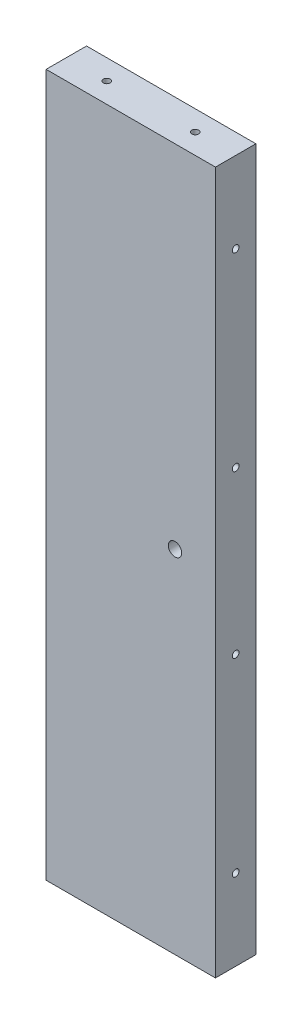
SolidWorks part; units mm, degrees
material "Beech"
ref_plane "Front Plane" through (0, 0, 0) normal (0, 0, 1) x (1, 0, 0)
ref_plane "Top Plane" through (0, 0, 0) normal (0, 1, 0) x (1, 0, 0)
ref_plane "Right Plane" through (0, 0, 0) normal (1, 0, 0) x (0, 0, -1)
sketch "Sketch1" plane through (0, 0, 0) normal (0, 0, 1) x (1, 0, 0)
  line L1 (209.353, 93.45) -> (289.1466, 93.45)
  line L2 (209.353, 93.45) -> (209.353, -237.5)
  line L3 (209.353, -237.5) -> (289.1466, -237.5)
  line L4 (289.1466, 93.45) -> (289.1466, -237.5)
  dimension "D1" = 79.7937
extrude "Boss-Extrude1" add sketch "Sketch1" along normal blind 19.05
hole_wizard "1/4 (0.25) Diameter Hole1" positions "Sketch10" profile "Sketch11" hole size "1/4" standard "ANSI Inch" end condition through all
sketch "Sketch10" plane through (0, 0, 0) normal (0, 0, -1) x (-1, 0, 0)
  point P0 (-270.0966, -72.025)
sketch "Sketch11" plane through (270.0966, -72.025, 0) normal (1, 0, 0) x (0, 1, 0)
  line L0 (0, 0) -> (0, 19.05)
  line L1 (0, 19.05) -> (3.175, 19.05)
  line L2 (3.175, 19.05) -> (3.175, 0)
  line L5 (3.175, 0) -> (0, 0)
  line L11 (0, -6.35) -> (0, 107.95) construction
  dimension "Thru Hole Dia." = 6.35
  dimension "Thru Hole Depth" = 19.05
hole_wizard "Hole6" positions "Sketch16" profile "Sketch17" legacy
sketch "Sketch16" plane through (308.1966, -72.025, 609.9098) normal (1, 0, 0) x (0, -1, 0)
  line L0 (-175, 310.0628) -> (-175, 724.4414) construction
  line L3 (-81.55, 824.9675) -> (-81.55, 609.9098) construction
  line L7 (-165.475, 600.3848) -> (0, 600.3848) construction
  line L9 (-175, 376.7378) -> (0, 376.7378) construction
  line L12 (0, 3.9184) -> (0, 227.5654) construction
  point P20 (-81.55, 717.4386)
  point P22 (-81.55, 641.6598)
  point P24 (-81.55, 793.2175)
  point P27 (-175, 705.3914)
  point P29 (-175, 329.1128)
  point P32 (-175, 579.9652)
  point P34 (-175, 454.539)
  point P35 (-175, 517.2521)
  point P50 (-127.375, 600.3848)
  point P52 (-38.1, 600.3848)
  point P61 (-127.375, 376.7378)
  point P63 (-38.1, 376.7378)
  point P74 (38.1, 376.7378)
  point P75 (127.375, 376.7378)
  point P76 (38.1, 600.3848)
  point P77 (127.375, 600.3848)
  point P78 (175, 517.2521)
  point P79 (175, 454.539)
  point P80 (175, 579.9652)
  point P81 (175, 329.1128)
  point P82 (175, 705.3914)
  point P83 (81.55, 793.2175)
  point P84 (81.55, 641.6598)
  point P85 (81.55, 717.4386)
sketch "Sketch17" plane through (308.1966, -153.575, -107.5289) normal (0, 1, 0) x (0, 0, -1)
  line L0 (0, 0) -> (0, 39.0539)
  line L1 (0, 39.0539) -> (1.5875, 38.1)
  line L2 (1.5875, 38.1) -> (1.5875, 4.0177)
  line L3 (1.5875, 4.0177) -> (5.08, 0)
  line L4 (5.08, 0) -> (0, 0)
  line L5 (0, -14.3089) -> (0, 102.4216) construction
  line L6 (0, 39.0539) -> (-1.5875, 38.1) construction
  line L7 (-1.5875, 4.0177) -> (-5.08, 0) construction
  dimension "Diameter" = 3.175
  dimension "Depth" = 38.1
  dimension "C-Sink Diameter" = 10.16
  dimension "C-Sink Angle" = 82
  dimension "Drill Angle" = 118
hole_wizard "Hole7" positions "Sketch18" profile "Sketch19" legacy
sketch "Sketch18" plane through (-181.0394, 112.5, 386.2628) normal (0, 1, 0) x (0.9272, 0, -0.3746)
  line L0 (9.7688, 133.4475) -> (528.1685, 52.1167) construction
  line L5 (0.0093, 25.4) -> (517.3743, 25.4) construction
  line L8 (660.1216, 540.8653) -> (441.5979, 0) construction
  line L11 (698.7793, 525.2466) -> (486.5659, 0) construction
  line L15 (604.5365, 403.2872) -> (643.1942, 387.6685) construction
  line L17 (520.7568, 195.9254) -> (559.4145, 180.3066) construction
  line L19 (507.6737, 163.5435) -> (546.3314, 147.9247) construction
  point P17 (34.8618, 129.5107)
  point P19 (398.7112, 72.427)
  point P22 (25.4093, 25.4)
  point P24 (393.7093, 25.4)
  point P40 (604.5365, 403.2872)
  point P41 (643.1942, 387.6685)
  point P44 (520.7568, 195.9254)
  point P45 (559.4145, 180.3066)
  point P48 (507.6737, 163.5435)
  point P49 (546.3314, 147.9247)
sketch "Sketch19" plane through (270.0966, 112.5, 44.45) normal (1, 0, 0) x (0, 0, 1)
  line L0 (0, 0) -> (0, 40.64)
  line L1 (0, 40.64) -> (1.5875, 39.6861)
  line L2 (1.5875, 39.6861) -> (1.5875, 4.0177)
  line L3 (1.5875, 4.0177) -> (5.08, 0)
  line L4 (5.08, 0) -> (0, 0)
  line L5 (0, -14.3089) -> (0, 102.4216) construction
  line L6 (0, 40.64) -> (-1.5875, 39.6861) construction
  line L7 (-1.5875, 4.0177) -> (-5.08, 0) construction
  dimension "Diameter" = 3.175
  dimension "Depth" = 40.64
  dimension "C-Sink Diameter" = 10.16
  dimension "C-Sink Angle" = 82
  dimension "Drill Angle" = 118
hole_wizard "Hole8" positions "Sketch20" profile "Sketch21"
sketch "Sketch20" plane through (-181.0394, -163.1, 609.9098) normal (0, -1, 0) x (-0.9272, 0, 0.3746)
  point P1 (-659.7862, 411.7841)
  point P3 (-615.2409, 429.7815)
  point P5 (-711.4987, 766.922)
  point P7 (-796.2804, 732.668)
  point P9 (-889.1694, 1044.5267)
  point P11 (-923.7091, 1031.114)
sketch "Sketch21" plane through (276.4466, -163.1, -19.05) normal (1, 0, 0) x (0, 0, -1)
  line L0 (0, 0) -> (0, 39.0539)
  line L1 (0, 39.0539) -> (1.5875, 38.1)
  line L2 (1.5875, 38.1) -> (1.5875, 4.0177)
  line L3 (1.5875, 4.0177) -> (5.08, 0)
  line L4 (5.08, 0) -> (0, 0)
  line L5 (0, -14.3089) -> (0, 102.4216) construction
  line L6 (0, 39.0539) -> (-1.5875, 38.1) construction
  line L7 (-1.5875, 4.0177) -> (-5.08, 0) construction
  dimension "Diameter" = 3.175
  dimension "Depth" = 38.1
  dimension "C-Sink Diameter" = 10.16
  dimension "C-Sink Angle" = 82
  dimension "Drill Angle" = 118
